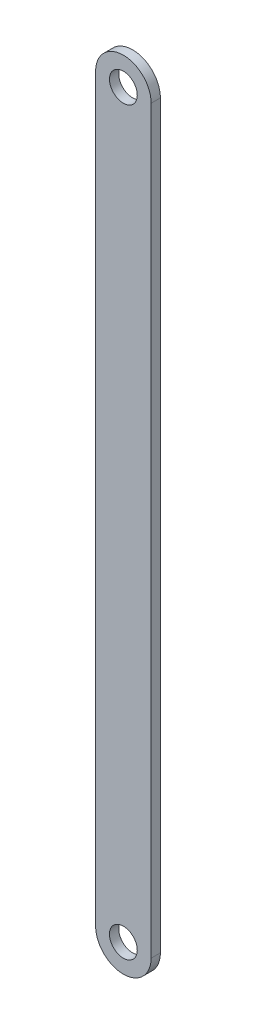
SolidWorks part; units mm, degrees
ref_plane "前视基准面" through (0, 0, 0) normal (0, 0, 1) x (1, 0, 0)
ref_plane "上视基准面" through (0, 0, 0) normal (0, 1, 0) x (1, 0, 0)
ref_plane "右视基准面" through (0, 0, 0) normal (1, 0, 0) x (0, 0, -1)
sketch "草图1" plane through (0, 0, 0) normal (0, 0, 1) x (1, 0, 0)
  line L0 (0, 0) -> (0, -160.01) construction
  line L1 (6, 0) -> (6, -160.01)
  line L2 (-6, -160.01) -> (-6, 0)
  circle A0 centre (0, 0) radius 3
  circle A1 centre (0, -160.01) radius 3
  arc A2 (6, -160.01) -> (-6, -160.01) centre (0, -160.01) cw
  arc A3 (6, 0) -> (-6, 0) centre (0, 0) ccw
extrude "凸台-拉伸1" add sketch "草图1" along normal blind 2 contours L1 A2 L2 A3
